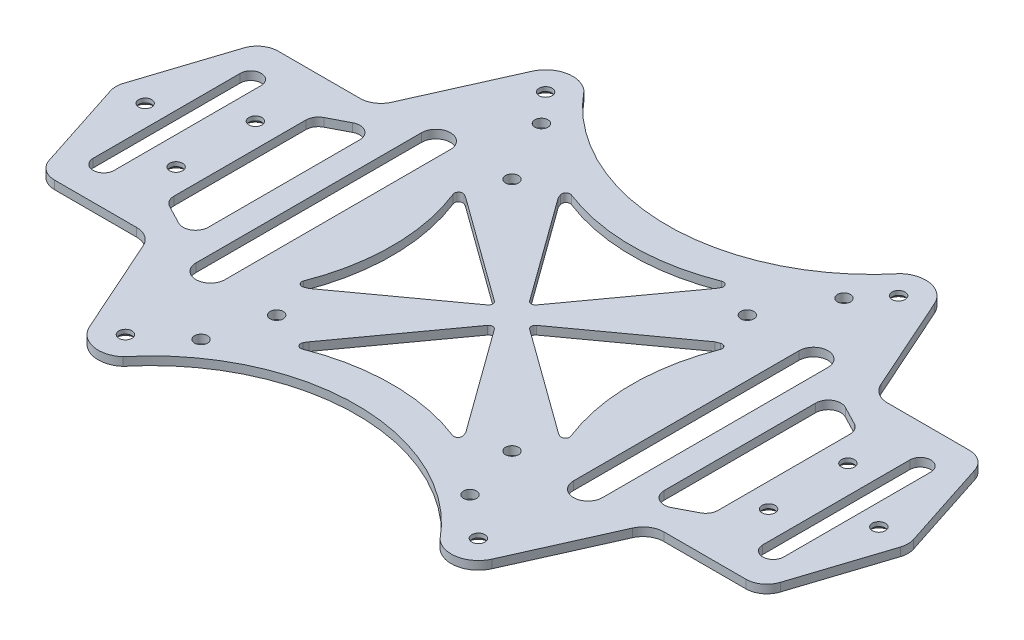
SolidWorks part; units mm, degrees
material "PPS"
ref_plane "前视基准面" through (0, 0, 0) normal (0, 0, 1) x (1, 0, 0)
ref_plane "上视基准面" through (0, 0, 0) normal (0, 1, 0) x (1, 0, 0)
ref_plane "右视基准面" through (0, 0, 0) normal (1, 0, 0) x (0, 0, -1)
sketch "参考" plane through (0, 0, 0) normal (0, 1, 0) x (1, 0, 0)
  line L3 (-133.7177, 0) -> (146.3754, 0) construction
  line L56 (0, 96.0639) -> (0, -115.1457) construction
  line L177 (114.5911, 7.4683) -> (114.5911, -7.4683)
  line L178 (114.5911, 7.4683) -> (43.1936, 17.6463)
  line L179 (114.5911, -7.4683) -> (43.1936, -17.6463)
  line L180 (-114.5911, -7.4683) -> (-43.1936, -17.6463)
  line L181 (-114.5911, 7.4683) -> (-114.5911, -7.4683)
  line L182 (-114.5911, 7.4683) -> (-43.1936, 17.6463)
  arc A18 (-37.7098, 54.831) -> (37.7098, 54.831) centre (0, 111.5317) ccw
  arc A20 (48.2756, 48.4632) -> (43.1936, 17.6463) centre (246.1791, 0) ccw
  arc A21 (48.2756, 48.4632) -> (37.7098, 54.831) centre (42, 50) ccw
  arc A22 (-37.7098, -54.831) -> (37.7098, -54.831) centre (0, -111.5317) cw
  arc A23 (48.2756, -48.4632) -> (43.1936, -17.6463) centre (246.1791, 0) cw
  arc A24 (48.2756, -48.4632) -> (37.7098, -54.831) centre (42, -50) cw
  arc A26 (-48.2756, -48.4632) -> (-37.7098, -54.831) centre (-42, -50) ccw
  arc A27 (-48.2756, -48.4632) -> (-43.1936, -17.6463) centre (-246.1791, 0) ccw
  arc A28 (-48.2756, 48.4632) -> (-37.7098, 54.831) centre (-42, 50) cw
  arc A30 (-48.2756, 48.4632) -> (-43.1936, 17.6463) centre (-246.1791, 0) cw
  dimension "D11" = 50
  dimension "D12" = 42
sketch "草图1" plane through (0, 0, 0) normal (0, 1, 0) x (1, 0, 0)
  line L0 (-160.1541, 0) -> (172.3115, 0) construction
  line L1 (0, 124.2182) -> (0, 50.8906) construction
  line L2 (79.6696, -17.5) -> (79.6696, 17.5) construction
  line L3 (77.1696, -17.5) -> (77.1696, 17.5)
  line L4 (82.1696, -17.5) -> (82.1696, 17.5)
  line L5 (-133.7177, 0) -> (146.3754, 0) construction
  line L6 (47.9, 52.6334) -> (59.525, 26.5883)
  line L7 (59.525, 26.5883) -> (85.8696, 26.5883)
  line L8 (85.8696, 26.5883) -> (94.5058, 0)
  line L9 (59.525, -26.5883) -> (85.8696, -26.5883)
  line L10 (47.9, -52.6334) -> (59.525, -26.5883)
  line L11 (85.8696, -26.5883) -> (94.5058, 0)
  line L12 (-47.9, -52.6334) -> (-59.525, -26.5883)
  line L13 (-59.525, -26.5883) -> (-85.8696, -26.5883)
  line L14 (-85.8696, -26.5883) -> (-94.5058, 0)
  line L15 (-85.8696, 26.5883) -> (-94.5058, 0)
  line L16 (-47.9, 52.6334) -> (-59.525, 26.5883)
  line L17 (-59.525, 26.5883) -> (-85.8696, 26.5883)
  line L18 (-79.6696, -17.5) -> (-79.6696, 17.5) construction
  line L19 (-77.1696, -17.5) -> (-77.1696, 17.5)
  line L20 (-82.1696, -17.5) -> (-82.1696, 17.5)
  line L21 (-29.6302, 18.6447) -> (-3.8912, 0)
  line L22 (18.6447, 29.6302) -> (0, 3.8912)
  line L23 (-29.6302, -18.6447) -> (-3.8912, 0)
  line L24 (-18.6447, 29.6302) -> (0, 3.8912)
  line L25 (0, 96.0639) -> (0, -115.1457) construction
  line L26 (29.6302, -18.6447) -> (3.8912, 0)
  line L27 (29.6302, 18.6447) -> (3.8912, 0)
  line L28 (-18.6447, -29.6302) -> (0, -3.8912)
  line L29 (18.6447, -29.6302) -> (0, -3.8912)
  line L30 (44.9192, -26.8293) -> (44.9192, 26.8293) construction
  line L31 (41.4687, -26.8293) -> (41.4687, 26.8293)
  line L32 (48.3697, -26.8293) -> (48.3697, 26.8293)
  line L39 (-44.9192, -26.8293) -> (-44.9192, 26.8293) construction
  line L40 (-41.4687, -26.8293) -> (-41.4687, 26.8293)
  line L41 (-48.3697, -26.8293) -> (-48.3697, 26.8293)
  line L48 (0, -50.8906) -> (0, -143.4382) construction
  line L53 (0, 44.9191) -> (0, -44.9191) construction
  circle A6 centre (42, 50) radius 1.55
  circle A7 centre (42, -50) radius 1.55
  circle A8 centre (-42, -50) radius 1.55
  circle A9 centre (-42, 50) radius 1.55
  circle A10 centre (36, 43) radius 1.55
  circle A11 centre (32, -42) radius 1.55
  circle A12 centre (-32, -42) radius 1.55
  circle A13 centre (-36, 43) radius 1.55
  arc A18 (77.1696, -17.5) -> (82.1696, -17.5) centre (79.6696, -17.5) ccw
  arc A19 (82.1696, 17.5) -> (77.1696, 17.5) centre (79.6696, 17.5) ccw
  circle A20 centre (70.5, 9.4358) radius 1.55
  circle A21 centre (70.5, -9.4358) radius 1.55
  circle A22 centre (-70.5, -9.4358) radius 1.55
  circle A23 centre (-70.5, 9.4358) radius 1.55
  circle A24 centre (87.3, 0) radius 1.55
  arc A25 (48.2756, 48.4632) -> (37.7098, 54.831) centre (42, 50) ccw construction
  arc A29 (-77.1696, -17.5) -> (-82.1696, -17.5) centre (-79.6696, -17.5) cw
  arc A30 (-82.1696, 17.5) -> (-77.1696, 17.5) centre (-79.6696, 17.5) cw
  circle A31 centre (-87.3, 0) radius 1.55
  arc A33 (-29.6302, 18.6447) -> (-32.6996, 19.7586) centre (-33.1107, 13.84) ccw
  arc A34 (-29.6302, -18.6447) -> (-32.6996, -19.7586) centre (-43.9211, 15.9492) cw
  arc A35 (-32.6996, -19.7586) -> (-32.6996, 19.7586) centre (-77.266, 0) ccw
  arc A36 (-18.6447, 29.6302) -> (-19.7586, 32.6996) centre (15.9492, 43.9211) cw
  arc A37 (-19.7586, 32.6996) -> (19.7586, 32.6996) centre (0, 77.266) ccw
  arc A38 (18.6447, 29.6302) -> (19.7586, 32.6996) centre (13.84, 33.1107) ccw
  arc A39 (29.6302, 18.6447) -> (32.6996, 19.7586) centre (43.9211, -15.9492) cw
  arc A40 (32.6996, 19.7586) -> (32.6996, -19.7586) centre (77.266, 0) ccw
  arc A41 (29.6302, -18.6447) -> (32.6996, -19.7586) centre (33.1107, -13.84) ccw
  arc A42 (18.6447, -29.6302) -> (19.7586, -32.6996) centre (-15.9492, -43.9211) cw
  arc A43 (19.7586, -32.6996) -> (-19.7586, -32.6996) centre (0, -77.266) ccw
  arc A44 (-18.6447, -29.6302) -> (-19.7586, -32.6996) centre (-13.84, -33.1107) ccw
  arc A45 (41.4687, -26.8293) -> (48.3697, -26.8293) centre (44.9192, -26.8293) ccw
  arc A46 (48.3697, 26.8293) -> (41.4687, 26.8293) centre (44.9192, 26.8293) ccw
  arc A51 (-41.4687, -26.8293) -> (-48.3697, -26.8293) centre (-44.9192, -26.8293) cw
  arc A52 (-48.3697, 26.8293) -> (-41.4687, 26.8293) centre (-44.9192, 26.8293) cw
  circle A55 centre (28, 28) radius 1.55
  circle A56 centre (28, -28) radius 1.55
  circle A57 centre (-28, -28) radius 1.55
  circle A58 centre (-28, 28) radius 1.55
  arc A59 (37.7098, 54.831) -> (-37.7098, 54.831) centre (0, 85.7265) cw
  arc A60 (37.7098, 54.831) -> (47.9, 52.6334) centre (42, 50) cw
  arc A61 (-37.7098, 54.831) -> (-47.9, 52.6334) centre (-42, 50) ccw
  arc A62 (-37.7098, -54.831) -> (-47.9, -52.6334) centre (-42, -50) cw
  arc A63 (37.7098, -54.831) -> (47.9, -52.6334) centre (42, -50) ccw
  arc A64 (37.7098, -54.831) -> (-37.7098, -54.831) centre (0, -85.7265) ccw
  point P30 (79.6696, 0)
  point P61 (4.9619, 0)
  point P63 (44.9192, 0)
  point P78 (-79.6696, 0)
  point P98 (0, 0)
  point P116 (-22.7886, -32.0712)
  point P117 (-19.7586, -32.9712)
  point P118 (-3.8912, 0)
  point P136 (-44.9192, 0)
  dimension "D1" = 50
  dimension "D3" = 3.1
  dimension "D8" = 2.5
  dimension "D10" = 3.1
  dimension "D12" = 3.1
  dimension "D15" = 48.75
  dimension "D18" = 3.1
  dimension "D19" = 28
  dimension "D2" = 42
  dimension "D4" = 36
  dimension "D5" = 32
  dimension "D6" = 42
  dimension "D7" = 43
  dimension "D9" = 35
  dimension "D11" = 70.5
  dimension "D13" = 87.3
  dimension "D14" = 4
  dimension "D20" = 28
  dimension "D21" = 4
extrude "凸台-拉伸1" add sketch "草图1" along normal blind 2
chamfer "倒角2" distance 1 angle 45 10 edges at (-70.5, 0, 10.9858) (-70.5, 0, -10.9858) (70.5, 0, 7.8858) (70.5, 0, -7.8858) (-87.3, 0, -1.55) (87.3, 0, 1.55) (-42, 0, 51.55) (42, 0, 48.45) (-42, 0, -51.55) (42, 0, -48.45)
sketch "减重草图镂空-如果影响结构强度则取消" plane through (0, 0, 0) normal (0, -1, 0) x (1, 0, 0)
  line L0 (0, 0) -> (0, 77.9145) construction
  line L1 (0, 0) -> (127.571, 0) construction
  line L2 (-64.75, 17.5) -> (-54.25, 22.966)
  line L3 (-54.25, 22.966) -> (-54.25, -22.966)
  line L4 (-54.25, -22.966) -> (-64.75, -17.5)
  line L5 (-64.75, -17.5) -> (-64.75, 17.5)
  line L6 (54.25, -22.966) -> (64.75, -17.5)
  line L7 (54.25, 22.966) -> (54.25, -22.966)
  line L8 (64.75, 17.5) -> (54.25, 22.966)
  line L9 (64.75, -17.5) -> (64.75, 17.5)
  circle A1 centre (-70.5, 9.4358) radius 1.55 construction
  dimension "D1" = 5.75
  dimension "D2" = 54.25
  dimension "D3" = 62.5
  dimension "D4" = 17.5
extrude "减重-如果影响结构强度则取消" cut sketch "减重草图镂空-如果影响结构强度则取消" against normal through all
fillet "圆角2" radius 3 8 edges at (64.75, 1, 17.5) (64.75, 1, -17.5) (54.25, 1, -22.966) (54.25, 1, 22.966) (-54.25, 1, -22.966) (-64.75, 1, -17.5) (-64.75, 1, 17.5) (-54.25, 1, 22.966)
fillet "圆角3" radius 5 10 edges at (59.525, 1, -26.5883) (85.8696, 1, -26.5883) (94.5058, 1, 0) (85.8696, 1, 26.5883) (59.525, 1, 26.5883) (-59.525, 1, 26.5883) (-85.8696, 1, -26.5883) (-94.5058, 1, 0) (-85.8696, 1, 26.5883) (-59.525, 1, -26.5883)
fillet "圆角4" radius 1 12 edges at (0, 1, -3.8912) (-19.7586, 1, 32.6996) (-32.6996, 1, 19.7586) (-3.8912, 1, 0) (0, 1, 3.8912) (-32.6996, 1, -19.7586) (19.7586, 1, 32.6996) (32.6996, 1, 19.7586) (3.8912, 1, 0) (-19.7586, 1, -32.6996) (19.7586, 1, -32.6996) (32.6996, 1, -19.7586)
